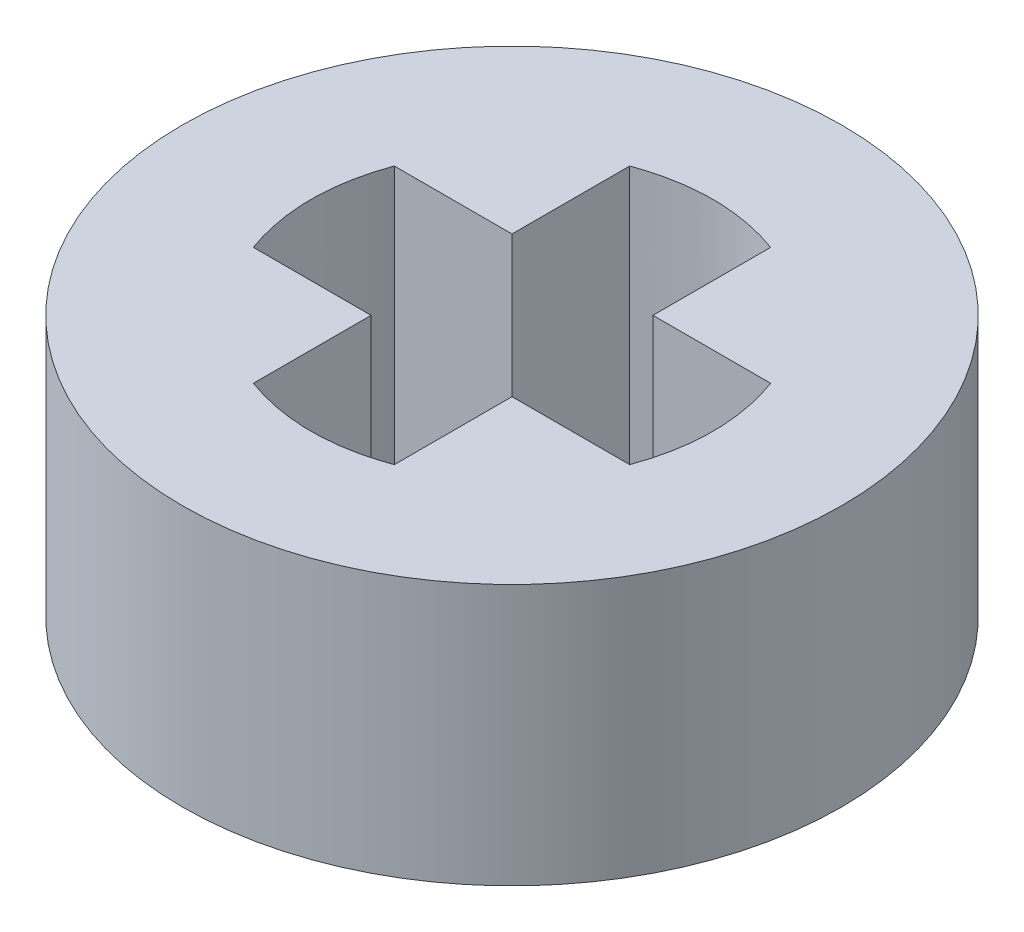
SolidWorks part; units mm, degrees
ref_plane "Front Plane" through (0, 0, 0) normal (0, 0, 1) x (1, 0, 0)
ref_plane "Top Plane" through (0, 0, 0) normal (0, 1, 0) x (1, 0, 0)
ref_plane "Right Plane" through (0, 0, 0) normal (1, 0, 0) x (0, 0, -1)
sketch "Sketch1" plane through (0, 0, 0) normal (0, 1, 0) x (1, 0, 0)
  circle A0 centre (0, 0) radius 3.79
  dimension "D1" = 7.58
extrude "Boss-Extrude1" add sketch "Sketch1" along normal blind 3
sketch "Sketch2" plane through (0, 3, 0) normal (0, 1, 0) x (1, 0, 0)
  line L0 (-2.1633, 0.81) -> (-0.81, 0.81)
  line L1 (2.1633, -0.81) -> (-2.1633, -0.81) construction
  line L2 (2.1633, -0.81) -> (2.1633, 0.81) construction
  line L3 (2.1633, 0.81) -> (-2.1633, 0.81) construction
  line L4 (-2.1633, -0.81) -> (-2.1633, 0.81) construction
  line L5 (2.1633, -0.81) -> (-2.1633, 0.81) construction
  line L6 (2.1633, 0.81) -> (-2.1633, -0.81) construction
  line L7 (-0.81, -2.1633) -> (0.81, -2.1633) construction
  line L8 (-0.81, -2.1633) -> (-0.81, 2.1633) construction
  line L9 (-0.81, 2.1633) -> (0.81, 2.1633) construction
  line L10 (0.81, -2.1633) -> (0.81, 2.1633) construction
  line L11 (-0.81, -2.1633) -> (0.81, 2.1633) construction
  line L12 (-0.81, 2.1633) -> (0.81, -2.1633) construction
  line L13 (-0.81, 0.81) -> (-0.81, 2.1633)
  line L14 (0.81, 2.1633) -> (0.81, 0.81)
  line L15 (0.81, 0.81) -> (2.1633, 0.81)
  line L16 (2.1633, -0.81) -> (0.81, -0.81)
  line L17 (0.81, -0.81) -> (0.81, -2.1633)
  line L18 (-0.81, -2.1633) -> (-0.81, -0.81)
  line L19 (-0.81, -0.81) -> (-2.1633, -0.81)
  circle A0 centre (0, 0) radius 2.31 construction
  spline S0 degree 2 poles (-2.1633, -0.81) (-2.4567, 0) (-2.1633, 0.81) knots 0 0 0 1 1 1
  spline S1 degree 2 poles (-0.81, 2.1633) (0, 2.4567) (0.81, 2.1633) knots 0 0 0 1 1 1
  spline S2 degree 2 poles (2.1633, 0.81) (2.4567, 0) (2.1633, -0.81) knots 0 0 0 1 1 1
  spline S3 degree 2 poles (0.81, -2.1633) (0, -2.4567) (-0.81, -2.1633) knots 0 0 0 1 1 1
  dimension "D1" = 4.62
  dimension "D2" = 1.62
  dimension "D3" = 1.62
extrude "Cut-Extrude1" cut sketch "Sketch2" against normal blind 3
